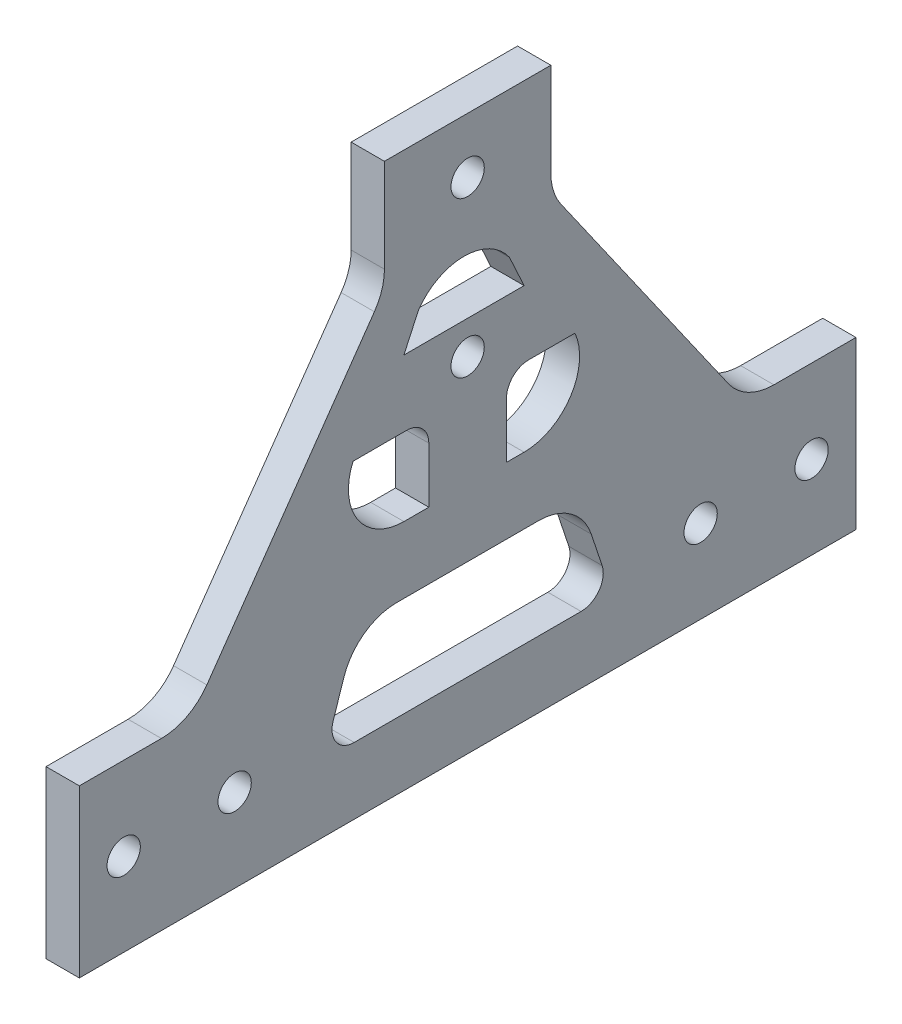
SolidWorks part; units mm, degrees
ref_plane "前视基准面" through (0, 0, 0) normal (0, 0, 1) x (1, 0, 0)
ref_plane "上视基准面" through (0, 0, 0) normal (0, 1, 0) x (1, 0, 0)
ref_plane "右视基准面" through (0, 0, 0) normal (1, 0, 0) x (0, 0, -1)
sketch "草图2" plane through (0, 0, 0) normal (1, 0, 0) x (0, 0, -1)
  line L0 (0, 0) -> (0, -15)
  line L2 (70, -15) -> (70, 0)
  line L3 (70, 0) -> (62.6033, 0)
  line L4 (58.5071, 2.1327) -> (43.4038, 23.7088)
  line L5 (42.5, 26.5761) -> (42.5, 35)
  line L6 (42.5, 35) -> (27.5, 35)
  line L7 (27.5, 35) -> (27.5, 26.5761)
  line L8 (26.5962, 23.7088) -> (11.4929, 2.1327)
  line L9 (7.3967, 0) -> (0, 0)
  line L10 (0, -15) -> (20, -15)
  line L11 (22.8775, -6.3675) -> (23.8604, -3.4189)
  line L12 (46.1396, -3.4189) -> (47.1225, -6.3675)
  line L13 (50, -15) -> (70, -15)
  line L14 (28.6038, 0) -> (41.3962, 0)
  line L16 (29.2562, 6) -> (31.5, 6)
  line L18 (24.6737, 13) -> (29.5, 13)
  line L20 (30.5775, 21.8673) -> (29.2562, 19)
  line L21 (29.2562, 19) -> (40.0911, 19)
  line L22 (40.0911, 19) -> (38.7698, 21.8673)
  line L23 (31.5, 11) -> (31.5, 6)
  line L24 (38.5, 11) -> (38.5, 6)
  line L25 (40.5, 13) -> (44.6737, 13)
  line L26 (38.5, 6) -> (40.0911, 6)
  line L27 (20, -15) -> (50, -15)
  line L28 (24.7749, -9) -> (45.2251, -9)
  arc A0 (41.3962, 0) -> (46.1396, -3.4189) centre (41.3962, -5) cw
  arc A1 (28.6038, 0) -> (23.8604, -3.4189) centre (28.6038, -5) ccw
  arc A2 (40.0911, 6) -> (44.6737, 13) centre (40.0911, 11) ccw
  arc A3 (24.6737, 13) -> (29.2562, 6) centre (29.2562, 11) ccw
  arc A4 (30.5775, 21.8673) -> (38.7698, 21.8673) centre (34.6737, 19) cw
  arc A5 (27.5, 26.5761) -> (26.5962, 23.7088) centre (22.5, 26.5761) cw
  arc A6 (43.4038, 23.7088) -> (42.5, 26.5761) centre (47.5, 26.5761) cw
  arc A7 (11.4929, 2.1327) -> (7.3967, 0) centre (7.3967, 5) cw
  arc A8 (62.6033, 0) -> (58.5071, 2.1327) centre (62.6033, 5) cw
  arc A9 (38.5, 11) -> (40.5, 13) centre (40.5, 11) cw
  arc A10 (31.5, 11) -> (29.5, 13) centre (29.5, 11) ccw
  arc A11 (45.2251, -9) -> (47.1225, -6.3675) centre (45.2251, -7) ccw
  arc A12 (24.7749, -9) -> (22.8775, -6.3675) centre (24.7749, -7) cw
  point P2 (35, 35)
  point P18 (35, 0)
  point P21 (45, 0)
  point P27 (25, 0)
  point P30 (50, 6)
  point P33 (20, 6)
  point P36 (35, 27.4286)
  point P39 (27.5, 25)
  point P42 (42.5, 25)
  point P47 (60, 0)
  point P53 (38.5, 13)
  dimension "D12" = 5
  dimension "D14" = 5
  dimension "D16" = 20
  dimension "D21" = 2
  dimension "D23" = 2
  dimension "D1" = 15
  dimension "D2" = 15
  dimension "D3" = 20
  dimension "D4" = 30
  dimension "D5" = 10
  dimension "D6" = 10
  dimension "D7" = 35
  dimension "D8" = 50
  dimension "D9" = 25
  dimension "D10" = 35
  dimension "D11" = 20
  dimension "D13" = 19
  dimension "D15" = 15
  dimension "D17" = 7
  dimension "D18" = 6
  dimension "D19" = 4
  dimension "D20" = 4
  dimension "D22" = 6
extrude "凸台-拉伸1" add sketch "草图2" along normal blind 3
sketch "草图3" plane through (3, 0, 0) normal (1, 0, 0) x (0, 0, -1)
  line L0 (42.5, 35) -> (27.5, 35) construction
  line L1 (0, 0) -> (0, -15) construction
  line L2 (70, -15) -> (70, 0) construction
  circle A0 centre (35, 30) radius 1.5
  circle A1 centre (66, -7.5) radius 1.5
  circle A2 centre (56, -7.5) radius 1.5
  circle A3 centre (14, -7.5) radius 1.5
  circle A4 centre (4, -7.5) radius 1.5
  circle A5 centre (35, 16) radius 1.5
  point P13 (35, 35)
  point P17 (0, -7.5)
  dimension "D1" = 3
  dimension "D7" = 3
  dimension "D2" = 5
  dimension "D3" = 4
  dimension "D4" = 10
  dimension "D5" = 4
  dimension "D6" = 10
  dimension "D8" = 14
extrude "切除-拉伸1" cut sketch "草图3" against normal blind 3
